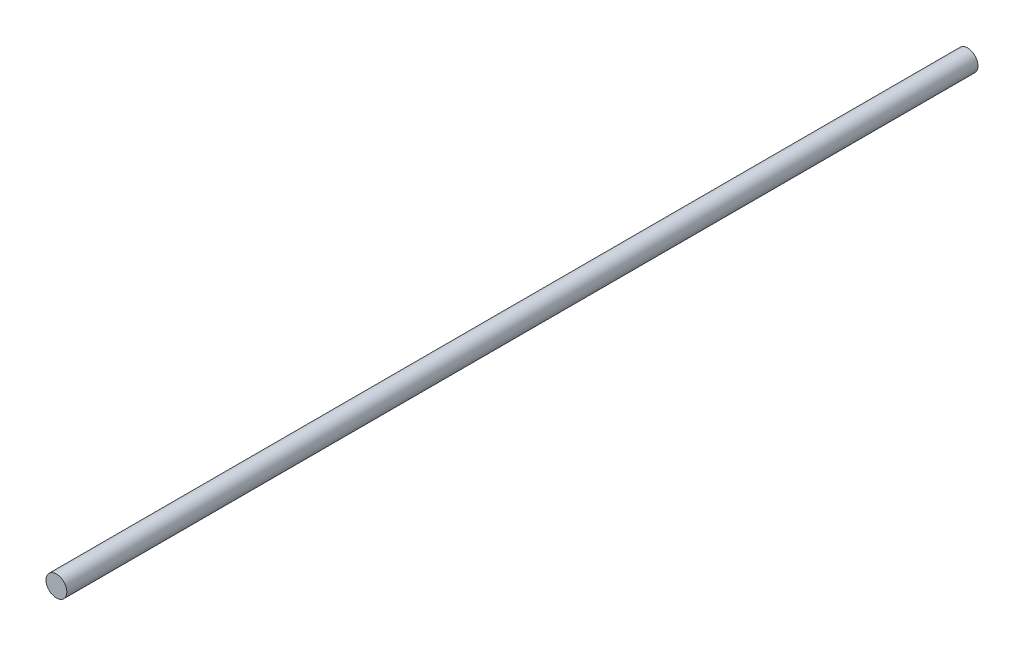
SolidWorks part; units mm, degrees
ref_plane "Front Plane" through (0, 0, 0) normal (0, 0, 1) x (1, 0, 0)
ref_plane "Top Plane" through (0, 0, 0) normal (0, 1, 0) x (1, 0, 0)
ref_plane "Right Plane" through (0, 0, 0) normal (1, 0, 0) x (0, 0, -1)
sketch "Sketch1" plane through (0, 0, 0) normal (0, 0, 1) x (1, 0, 0)
  circle A0 centre (0, 0) radius 4
  dimension "D1" = 8
extrude "Boss-Extrude1" add sketch "Sketch1" along normal mid plane 350
